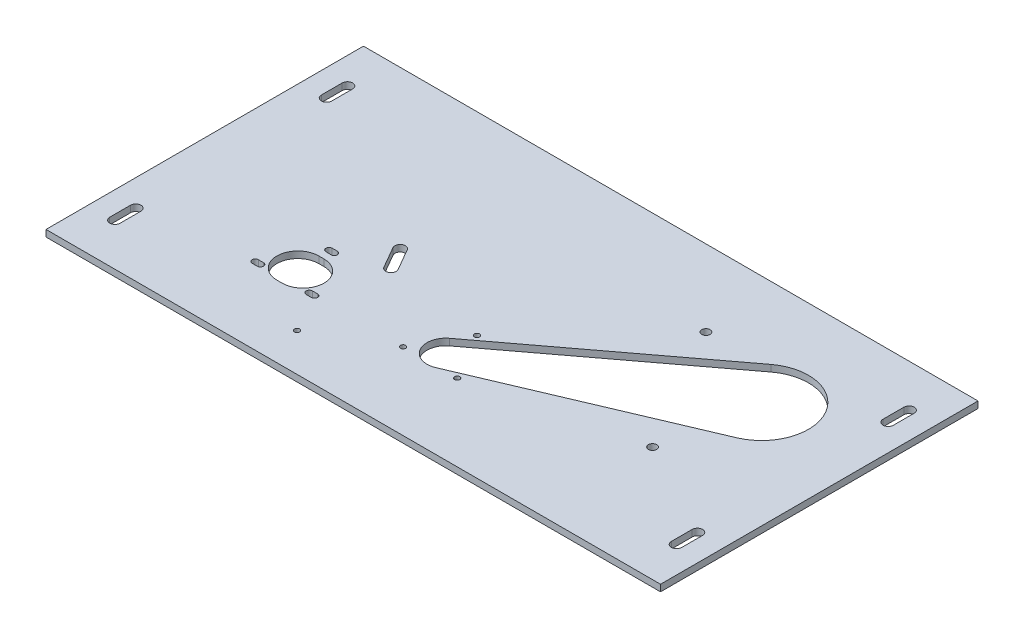
SolidWorks part; units mm, degrees
ref_plane "Alzado" through (0, 0, 0) normal (0, 0, 1) x (1, 0, 0)
ref_plane "Planta" through (0, 0, 0) normal (0, 1, 0) x (1, 0, 0)
ref_plane "Vista lateral" through (0, 0, 0) normal (1, 0, 0) x (0, 0, -1)
sketch "Croquis1" plane through (0, 0, 0) normal (0, 1, 0) x (1, 0, 0)
  line L1 (-147.5, 76.2) -> (147.5, 76.2)
  line L2 (-147.5, 76.2) -> (-147.5, -76.2)
  line L3 (-147.5, -76.2) -> (147.5, -76.2)
  line L4 (147.5, 76.2) -> (147.5, -76.2)
  line L5 (-147.5, 76.2) -> (147.5, -76.2) construction
  line L6 (-147.5, -76.2) -> (147.5, 76.2) construction
  point P0 (0, 0)
  dimension "D1" = 152.4
  dimension "D2" = 295
extrude "Saliente-Extruir1" add sketch "Croquis1" along normal blind 3.175
sketch "Croquis2" plane through (0, 3.175, 0) normal (0, 1, 0) x (1, 0, 0)
  line L0 (-147.5, 0) -> (0, 0) construction
  line L1 (-147.5, 76.2) -> (-147.5, -76.2) construction
  line L2 (0, 0) -> (0, 76.2) construction
  line L3 (147.5, 76.2) -> (-147.5, 76.2) construction
  line L4 (-147.5, -50.8) -> (147.5, -50.8) construction
  line L5 (147.5, -76.2) -> (147.5, 76.2) construction
  line L6 (-147.5, -76.2) -> (147.5, -76.2) construction
  line L7 (0, -31.8) -> (96.1288, 23.7) construction
  line L8 (-13.6399, 12.1312) -> (89.7537, 44.2331) construction
  line L9 (31.2256, -65.5781) -> (110.7234, 7.9124) construction
  line L10 (53.5487, 39.5309) -> (88.5487, -21.0909) construction
  line L11 (-5.4145, -24.6109) -> (82.5925, 41.6727)
  line L12 (3.5186, -40.0837) -> (104.9254, 2.9908)
  line L13 (0, 0) -> (0, -76.2) construction
  line L14 (-122.1, 76.2) -> (-122.1, -76.2) construction
  line L15 (122.1, 76.2) -> (122.1, -76.2) construction
  line L16 (-134.8, 76.2) -> (-134.8, -76.2) construction
  line L17 (-134.8, 55.8) -> (-134.8, 45.8) construction
  line L18 (-132.3, 55.8) -> (-132.3, 45.8)
  line L19 (-137.3, 55.8) -> (-137.3, 45.8)
  line L20 (-134.8, -55.8) -> (-134.8, -45.8) construction
  line L21 (-132.3, -55.8) -> (-132.3, -45.8)
  line L22 (-137.3, -55.8) -> (-137.3, -45.8)
  line L23 (134.8, -55.8) -> (134.8, -45.8) construction
  line L24 (132.3, -55.8) -> (132.3, -45.8)
  line L25 (137.3, -55.8) -> (137.3, -45.8)
  line L26 (134.8, 55.8) -> (134.8, 45.8) construction
  line L27 (132.3, 55.8) -> (132.3, 45.8)
  line L28 (137.3, 55.8) -> (137.3, 45.8)
  line L29 (0, -31.8) -> (-45.2498, -57.925) construction
  circle A0 centre (0, -31.8) radius 46 construction
  circle A1 centre (96.1288, 23.7) radius 21.5 construction
  circle A2 centre (0, -31.8) radius 9
  circle A3 centre (88.5487, -21.0909) radius 2
  circle A4 centre (53.5487, 39.5309) radius 2
  circle A5 centre (96.1288, 23.7) radius 22.5
  arc A6 (-132.3, 55.8) -> (-137.3, 55.8) centre (-134.8, 55.8) ccw
  arc A7 (-137.3, 45.8) -> (-132.3, 45.8) centre (-134.8, 45.8) ccw
  arc A8 (-132.3, -55.8) -> (-137.3, -55.8) centre (-134.8, -55.8) cw
  arc A9 (-137.3, -45.8) -> (-132.3, -45.8) centre (-134.8, -45.8) cw
  arc A10 (132.3, -55.8) -> (137.3, -55.8) centre (134.8, -55.8) ccw
  arc A11 (137.3, -45.8) -> (132.3, -45.8) centre (134.8, -45.8) ccw
  arc A12 (132.3, 55.8) -> (137.3, 55.8) centre (134.8, 55.8) cw
  arc A13 (137.3, 45.8) -> (132.3, 45.8) centre (134.8, 45.8) cw
  circle A14 centre (-45.2498, -57.925) radius 1.25
  point P26 (71.0487, 9.22)
  point P42 (-134.8, 50.8)
  point P50 (-134.8, -50.8)
  point P57 (134.8, -50.8)
  point P64 (134.8, 50.8)
  dimension "D2" = 92
  dimension "D4" = 43
  dimension "D5" = 18
  dimension "D7" = 4
  dimension "D9" = 45
  dimension "D14" = 2.5
  dimension "D17" = 2.5
  dimension "D1" = 25.4
  dimension "D3" = 111
  dimension "D6" = 35
  dimension "D8" = 82.04
  dimension "D10" = 25.4
  dimension "D11" = 30
  dimension "D12" = 19
  dimension "D13" = 12.7
  dimension "D15" = 10
  dimension "D16" = 50.8
  dimension "D18" = 52.25
extrude "Cortar-Extruir1" cut sketch "Croquis2" against normal blind 3.175 contours L19 A7 L18 A6 | A9 L22 A8 L21 | A2 | A5 | A4 | A3 | A13 L28 A12 L27 | L25 A11 L24 A10 | A5 L11 A2 L12 | A14
sketch "Croquis3" plane through (0, 3.175, 0) normal (0, 1, 0) x (1, 0, 0)
  line L0 (0, -31.8) -> (-68.5, -31.8) construction
  line L1 (-147.5, 0) -> (0, 0) construction
  line L2 (-147.5, 76.2) -> (-147.5, -76.2) construction
  line L3 (0, 0) -> (0, 76.2) construction
  line L4 (0, 0) -> (0, -31.8) construction
  line L5 (-68.5, -31.8) -> (-68.5, -12.395) construction
  line L6 (-68.5, -12.395) -> (0, -12.395) construction
  line L7 (-51.5, -12.395) -> (-51.5, -4.395) construction
  line L8 (-54.5, 0.8012) -> (-48.5, -9.5912) construction
  line L13 (-52.3349, 2.0512) -> (-46.3349, -8.3412)
  line L16 (-71, -16.8) -> (-68.5, -16.8) construction
  line L19 (-58.0096, -39.3) -> (-55.5096, -39.3) construction
  line L26 (-71, -15.3) -> (-68.5, -15.3)
  line L27 (-58.0096, -37.8) -> (-55.5096, -37.8)
  line L28 (-58.0096, -40.8) -> (-55.5096, -40.8)
  line L31 (-71, -18.3) -> (-68.5, -18.3)
  line L34 (-83.9904, -39.3) -> (-81.4904, -39.3) construction
  line L35 (-83.9904, -37.8) -> (-81.4904, -37.8)
  line L36 (-83.9904, -40.8) -> (-81.4904, -40.8)
  line L37 (-71, -31.8) -> (-68.5, -31.8) construction
  line L38 (-71, -21.75) -> (-68.5, -21.75)
  line L39 (-71, -41.85) -> (-68.5, -41.85)
  line L40 (-56.6651, -0.4488) -> (-50.6651, -10.8412)
  line L41 (-54.5, -64.4012) -> (-48.5, -54.0088) construction
  line L42 (-52.3349, -65.6512) -> (-46.3349, -55.2588) construction
  line L43 (-56.6651, -63.1512) -> (-50.6651, -52.7588) construction
  circle A0 centre (0, -16.8) radius 1.25
  circle A1 centre (12.9904, -39.3) radius 1.25
  circle A2 centre (-12.9904, -39.3) radius 1.25
  circle A3 centre (-68.5, -31.8) radius 19.405 construction
  circle A4 centre (-68.5, -16.8) radius 1.5 construction
  circle A5 centre (-55.5096, -39.3) radius 1.5 construction
  circle A6 centre (-81.4904, -39.3) radius 1.5 construction
  circle A7 centre (0, -31.8) radius 19.405 construction
  circle A8 centre (0, -31.8) radius 46 construction
  circle A15 centre (-68.5, -31.8) radius 10.05 construction
  arc A28 (-58.0096, -37.8) -> (-58.0096, -40.8) centre (-58.0096, -39.3) ccw
  arc A29 (-55.5096, -40.8) -> (-55.5096, -37.8) centre (-55.5096, -39.3) ccw
  arc A30 (-71, -15.3) -> (-71, -18.3) centre (-71, -16.8) ccw
  arc A31 (-68.5, -18.3) -> (-68.5, -15.3) centre (-68.5, -16.8) ccw
  arc A32 (-83.9904, -37.8) -> (-83.9904, -40.8) centre (-83.9904, -39.3) ccw
  arc A33 (-81.4904, -40.8) -> (-81.4904, -37.8) centre (-81.4904, -39.3) ccw
  arc A34 (-71, -21.75) -> (-71, -41.85) centre (-71, -31.8) ccw
  arc A35 (-68.5, -41.85) -> (-68.5, -21.75) centre (-68.5, -31.8) ccw
  arc A36 (-52.3349, 2.0512) -> (-56.6651, -0.4488) centre (-54.5, 0.8012) ccw
  arc A37 (-50.6651, -10.8412) -> (-46.3349, -8.3412) centre (-48.5, -9.5912) ccw
  arc A38 (-52.3349, -65.6512) -> (-56.6651, -63.1512) centre (-54.5, -64.4012) cw construction
  arc A39 (-50.6651, -52.7588) -> (-46.3349, -55.2588) centre (-48.5, -54.0088) cw construction
  point P16 (0, -31.8)
  point P26 (-68.5, -31.8)
  point P31 (-51.5, -4.395)
  point P39 (-51.5, -59.205)
  point P47 (-56.7596, -39.3)
  point P52 (-69.75, -16.8)
  point P58 (-82.7404, -39.3)
  point P64 (-69.75, -31.8)
  dimension "D2" = 2.5
  dimension "D4" = 38.81
  dimension "D8" = 92
  dimension "D11" = 2.5
  dimension "D13" = 20.1
  dimension "D15" = 2.5
  dimension "D16" = 2.5
  dimension "D19" = 1.5
  dimension "D1" = 15
  dimension "D6" = 15
  dimension "D7" = 68.5
  dimension "D9" = 8
  dimension "D10" = 17
  dimension "D12" = 12
  dimension "D14" = 2.5
  dimension "D17" = 2.5
  dimension "D18" = 30
  dimension "D3" = 3
  dimension "D5" = 3
extrude "Cortar-Extruir2" cut sketch "Croquis3" against normal through all
